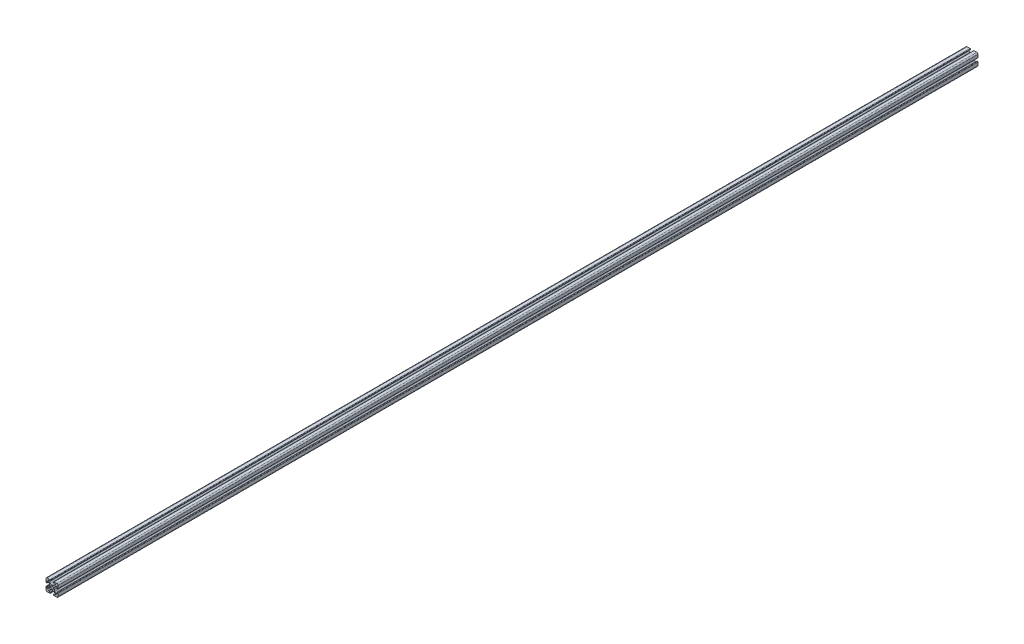
SolidWorks part; units mm, degrees
ref_plane "Front Plane" through (0, 0, 0) normal (0, 0, 1) x (1, 0, 0)
ref_plane "Top Plane" through (0, 0, 0) normal (0, 1, 0) x (1, 0, 0)
ref_plane "Right Plane" through (0, 0, 0) normal (1, 0, 0) x (0, 0, -1)
sketch "Sketch1" plane through (0, 0, 0) normal (0, 0, 1) x (1, 0, 0)
  line L0 (0, 0) -> (0, 10) construction
  line L1 (0, 0) -> (10, 0) construction
  line L2 (0, 0) -> (-10, 10) construction
  line L3 (-7.9302, 9.9988) -> (-3.2721, 9.8361)
  line L4 (-10, 10) -> (0, 10) construction
  line L6 (-2.8352, 8.0198) -> (-4.953, 8.0937)
  line L10 (0, 3.6) -> (-1.1022, 3.6)
  line L11 (-3.2236, 4.4787) -> (-5.5244, 6.7796)
  line L24 (0, 0) -> (-10, 0) construction
  line L25 (-10, 0) -> (0, 0) construction
  line L26 (0, 0) -> (0, -10) construction
  line L27 (-10, -10) -> (-10, 10) construction
  line L28 (0, 10) -> (10, 10) construction
  line L29 (-2.5249, 8.3091) -> (-2.5005, 9.0087)
  line L30 (-10, -10) -> (10, -10) construction
  arc A0 (-9.4142, 9.4142) -> (-7.9302, 9.9988) centre (-8, 8) cw
  arc A5 (-3.2721, 9.8361) -> (-2.5005, 9.0087) centre (-3.3, 9.0366) cw
  arc A6 (-1.1022, 3.6) -> (-3.2236, 4.4787) centre (-1.1022, 6.6) cw
  circle A16 centre (0, 0) radius 2.15
  arc A18 (-5.5244, 6.7796) -> (-4.953, 8.0937) centre (-4.9799, 7.3241) cw
  arc A20 (-2.8352, 8.0198) -> (-2.5249, 8.3091) centre (-2.8247, 8.3196) ccw
  point P15 (0, 0)
  point P42 (-2.3449, 3.6)
  point P80 (-10, 0)
  point P85 (0, -10)
  point P88 (0, -10)
  dimension "D11" = 2
  dimension "D15" = 3
  dimension "Center Hole Diameter" = 4.3
  dimension "D7" = 0.8
  dimension "D8" = 0.3
  dimension "D4" = 0.7701
  dimension "D1" = 45
  dimension "D2" = 2
  dimension "Rail Width" = 20
  dimension "T-Slot Depth" = 6.4
  dimension "D9" = 1.8
  dimension "Rail Height" = 20
  dimension "D23" = 7.2
  dimension "D5" = 11.5
  dimension "T-Slot Width" = 5
  dimension "D3" = 1.775
  dimension "D6" = 9.9598
sketch "Sketch2" plane through (0, 0, 0) normal (1, 0, 0) x (0, 0, -1)
  line L0 (-762, 0) -> (762, 0)
  line L1 (-762, -10) -> (-762, 10)
  line L2 (0, 0) -> (0, 10) construction
  line L3 (0, 0) -> (0, 10) construction
  line L4 (762, -10) -> (762, 10)
  point P0 (-732, 0)
  point P3 (0, 0)
  point P7 (732, 0)
  point P11 (-762, 0)
  point P14 (762, 0)
  dimension "D1" = 30
  dimension "Length" = 1524
sketch "Sketch3" plane through (0, 0, 0) normal (0, 0, 1) x (1, 0, 0)
  line L0 (-2.5249, 8.3091) -> (-2.5005, 9.0087) construction
  line L1 (0, 0) -> (-10, 10) construction
  line L2 (0, 0) -> (-10, 10) construction
  line L5 (-7.9302, 9.9988) -> (-3.2721, 9.8361) construction
  line L6 (-2.8352, 8.0198) -> (-4.953, 8.0937) construction
  line L17 (-2.5249, 8.3091) -> (-2.5005, 9.0087)
  line L19 (-2.8352, 8.0198) -> (-4.953, 8.0937)
  line L20 (0, 0) -> (0, 10) construction
  line L21 (-3.6, 0) -> (-2.15, 0)
  line L22 (-3.6, 0) -> (-3.6, 1.1022)
  line L23 (-4.4787, 3.2236) -> (-6.7796, 5.5244)
  line L42 (-3.2236, 4.4787) -> (-5.5244, 6.7796) construction
  line L43 (0, 3.6) -> (-1.1022, 3.6) construction
  line L44 (-7.9302, 9.9988) -> (-3.2721, 9.8361)
  line L47 (-3.2236, 4.4787) -> (-5.5244, 6.7796)
  line L48 (0, 3.6) -> (-1.1022, 3.6)
  line L59 (0, 3.6) -> (0, 2.15)
  line L60 (-9.9988, 7.9302) -> (-9.8361, 3.2721)
  line L61 (-8.0198, 2.8352) -> (-8.0937, 4.953)
  line L62 (-8.3091, 2.5249) -> (-9.0087, 2.5005)
  arc A0 (-7.9302, 9.9988) -> (-9.4142, 9.4142) centre (-8, 8) ccw construction
  arc A1 (-2.8352, 8.0198) -> (-2.5249, 8.3091) centre (-2.8247, 8.3196) ccw construction
  arc A3 (-2.8352, 8.0198) -> (-2.5249, 8.3091) centre (-2.8247, 8.3196) ccw
  arc A5 (-7.9302, 9.9988) -> (-9.9988, 7.9302) centre (-8, 8) ccw
  circle A13 centre (0, 0) radius 2.15 construction
  arc A14 (0, 2.15) -> (-2.15, 0) centre (0, 0) ccw
  arc A15 (-4.4787, 3.2236) -> (-3.6, 1.1022) centre (-6.6, 1.1022) cw
  arc A16 (-8.0937, 4.953) -> (-6.7796, 5.5244) centre (-7.3241, 4.9799) cw
  arc A17 (-9.0087, 2.5005) -> (-9.8361, 3.2721) centre (-9.0366, 3.3) cw
  arc A18 (-8.0198, 2.8352) -> (-8.3091, 2.5249) centre (-8.3196, 2.8247) cw
  arc A36 (-2.5005, 9.0087) -> (-3.2721, 9.8361) centre (-3.3, 9.0366) ccw construction
  arc A38 (-4.953, 8.0937) -> (-5.5244, 6.7796) centre (-4.9799, 7.3241) ccw construction
  arc A39 (-3.2236, 4.4787) -> (-1.1022, 3.6) centre (-1.1022, 6.6) ccw construction
  arc A41 (-2.5005, 9.0087) -> (-3.2721, 9.8361) centre (-3.3, 9.0366) ccw
  arc A43 (-4.953, 8.0937) -> (-5.5244, 6.7796) centre (-4.9799, 7.3241) ccw
  arc A44 (-3.2236, 4.4787) -> (-1.1022, 3.6) centre (-1.1022, 6.6) ccw
extrude "Boss-Extrude1" add sketch "Sketch3" along normal mid plane 1524
pattern_circular "CirPattern1" count 4 over 360 about axis through (0, 0, 0) along (0, 0, 1) of "Boss-Extrude1"
ref_plane "Contact Plane 1" through (0, 10, 0) normal (0, 1, 0) x (1, 0, 0)
ref_plane "Contact Plane 2" through (10, 0, 0) normal (1, 0, 0) x (0, 0, -1)
ref_plane "Contact Plane 3" through (0, -10, 0) normal (0, -1, 0) x (-1, 0, 0)
ref_plane "Contact Plane 4" through (-10, 0, 0) normal (-1, 0, 0) x (0, 0, 1)
equation "\"D1@Sketch2\"=\"Rail Width@Sketch1\"*1.5"
equation "\"D1@Boss-Extrude1\" = \"Length@Sketch2\""
